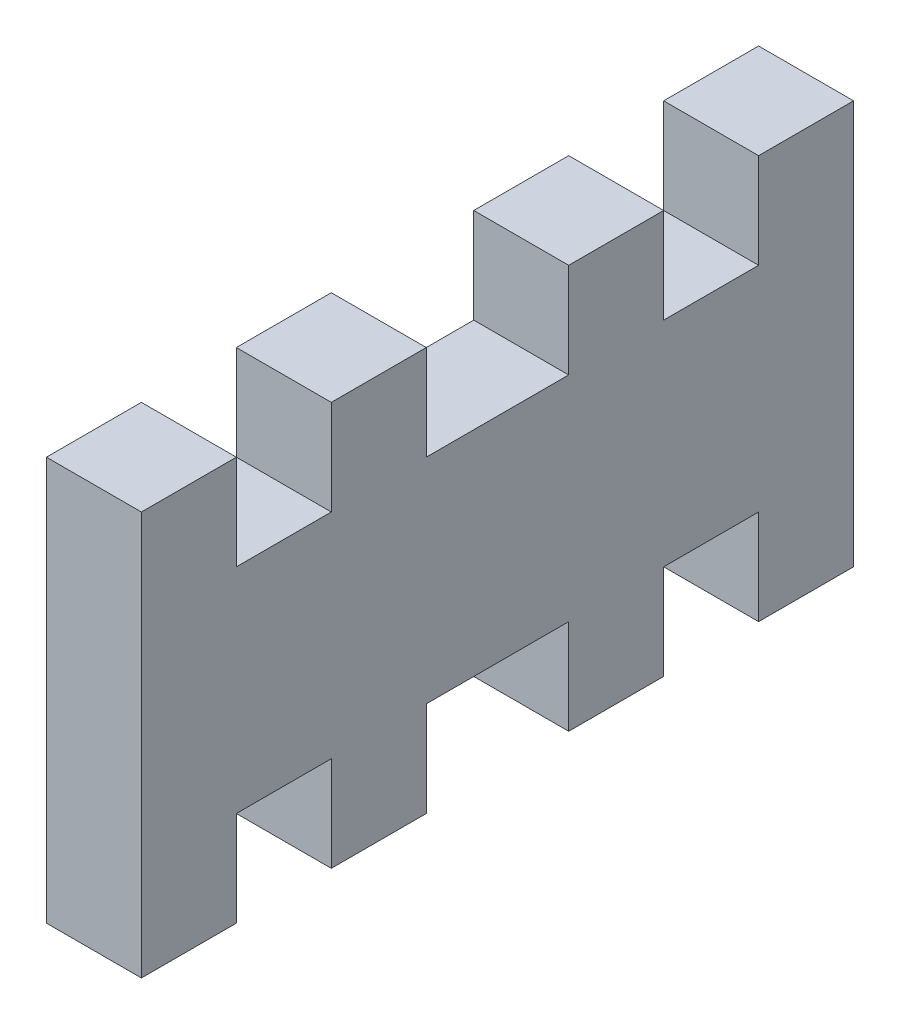
SolidWorks part; units mm, degrees
ref_plane "Front Plane" through (0, 0, 0) normal (0, 0, 1) x (1, 0, 0)
ref_plane "Top Plane" through (0, 0, 0) normal (0, 1, 0) x (1, 0, 0)
ref_plane "Right Plane" through (0, 0, 0) normal (1, 0, 0) x (0, 0, -1)
sketch "Sketch1" plane through (0, 0, 0) normal (1, 0, 0) x (0, 0, -1)
  line L1 (-13.6585, 15.7252) -> (24.4415, 15.7252)
  line L2 (-13.6585, 15.7252) -> (-13.6585, 4.2952)
  line L3 (-13.6585, 4.2952) -> (24.4415, 4.2952)
  line L4 (24.4415, 15.7252) -> (24.4415, 4.2952)
  dimension "D1" = 38.1
  dimension "D2" = 11.43
extrude "Boss-Extrude1" add sketch "Sketch1" along normal blind 5.08
sketch "Sketch2" plane through (5.08, 0, 0) normal (1, 0, 0) x (0, 0, -1)
  line L0 (5.3915, 15.7252) -> (5.3915, 4.2952) construction
  line L1 (24.4415, 15.7252) -> (-13.6585, 15.7252) construction
  line L2 (-13.6585, 4.2952) -> (24.4415, 4.2952) construction
  line L3 (-13.6585, 10.0102) -> (24.4415, 10.0102) construction
  line L4 (-13.6585, 15.7252) -> (-13.6585, 4.2952) construction
  line L5 (24.4415, 4.2952) -> (24.4415, 15.7252) construction
  line L6 (-13.6585, 15.7252) -> (-13.6585, 20.8052)
  line L7 (9.2015, 15.7252) -> (14.2815, 15.7252)
  line L8 (9.2015, 15.7252) -> (9.2015, 20.8052)
  line L9 (9.2015, 20.8052) -> (14.2815, 20.8052)
  line L10 (14.2815, 15.7252) -> (14.2815, 20.8052)
  line L11 (19.3615, 15.7252) -> (24.4415, 15.7252)
  line L12 (19.3615, 15.7252) -> (19.3615, 20.8052)
  line L13 (19.3615, 20.8052) -> (24.4415, 20.8052)
  line L14 (24.4415, 15.7252) -> (24.4415, 20.8052)
  line L15 (-8.5785, 20.8052) -> (-13.6585, 20.8052)
  line L16 (-8.5785, 15.7252) -> (-8.5785, 20.8052)
  line L17 (-8.5785, 15.7252) -> (-13.6585, 15.7252)
  line L18 (-3.4985, 15.7252) -> (-3.4985, 20.8052)
  line L19 (1.5815, 20.8052) -> (-3.4985, 20.8052)
  line L20 (1.5815, 15.7252) -> (1.5815, 20.8052)
  line L21 (1.5815, 15.7252) -> (-3.4985, 15.7252)
  line L22 (1.5815, 4.2952) -> (-3.4985, 4.2952)
  line L23 (1.5815, 4.2952) -> (1.5815, -0.7848)
  line L24 (1.5815, -0.7848) -> (-3.4985, -0.7848)
  line L25 (-3.4985, 4.2952) -> (-3.4985, -0.7848)
  line L26 (-8.5785, 4.2952) -> (-13.6585, 4.2952)
  line L27 (-8.5785, 4.2952) -> (-8.5785, -0.7848)
  line L28 (-8.5785, -0.7848) -> (-13.6585, -0.7848)
  line L29 (24.4415, 4.2952) -> (24.4415, -0.7848)
  line L30 (19.3615, -0.7848) -> (24.4415, -0.7848)
  line L31 (19.3615, 4.2952) -> (19.3615, -0.7848)
  line L32 (19.3615, 4.2952) -> (24.4415, 4.2952)
  line L33 (14.2815, 4.2952) -> (14.2815, -0.7848)
  line L34 (9.2015, -0.7848) -> (14.2815, -0.7848)
  line L35 (9.2015, 4.2952) -> (9.2015, -0.7848)
  line L36 (9.2015, 4.2952) -> (14.2815, 4.2952)
  line L37 (-13.6585, 4.2952) -> (-13.6585, -0.7848)
  dimension "D1" = 5.08
  dimension "D2" = 5.08
  dimension "D3" = 5.08
  dimension "D4" = 3.81
  dimension "D5" = 5.08
  dimension "D6" = 5.08
extrude "Boss-Extrude2" add sketch "Sketch2" against normal blind 5.08
